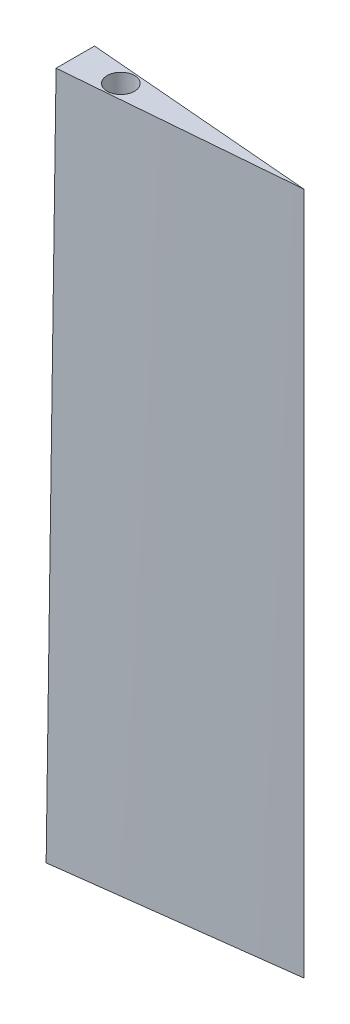
SolidWorks part; units mm, degrees
material "Полиуретановый жесткий пенопласт"
ref_plane "Спереди" through (0, 0, 0) normal (0, 0, 1) x (1, 0, 0)
ref_plane "Сверху" through (0, 0, 0) normal (0, 1, 0) x (1, 0, 0)
ref_plane "Справа" through (0, 0, 0) normal (1, 0, 0) x (0, 0, -1)
sketch "Эскиз1" plane through (0, 0, 0) normal (0, 1, 0) x (1, 0, 0)
  line L0 (0, 3.2) -> (0, -3.2)
  line L1 (0, 0) -> (25.09, 0) construction
  line L2 (0, 3.2) -> (25.09, 0)
  line L3 (25.09, 0) -> (0, -3.2)
  dimension "D1" = 6.4
  dimension "D2" = 3.2
  dimension "D3" = 25.09
ref_plane "Плоскость1" through (0, 75, 0) normal (0, 1, 0) x (1, 0, 0)
sketch "Эскиз2" plane through (0, 75, 0) normal (0, 1, 0) x (1, 0, 0)
  line L0 (0, 2.11) -> (0, -2.11)
  line L1 (0, 3.2) -> (0, -3.2) construction
  line L2 (0, 2.11) -> (25.09, 0)
  line L3 (25.09, 0) -> (0, -2.11)
  dimension "D1" = 4.22
  dimension "D2" = 2.11
loft "По сечениям1" add profiles "Эскиз1", "Эскиз2"
sketch "Эскиз3" plane through (0, 0, 0) normal (0, -1, 0) x (1, 0, 0)
  line L0 (0, 0) -> (25.09, 0) construction
  line L1 (-1.0057, 0) -> (27.8146, 0) construction
  circle A0 centre (5, 0) radius 1.5
  point P7 (0, 0)
  dimension "D1" = 3
  dimension "D2" = 5
extrude "Вырез-Вытянуть1" cut sketch "Эскиз3" against normal through all
